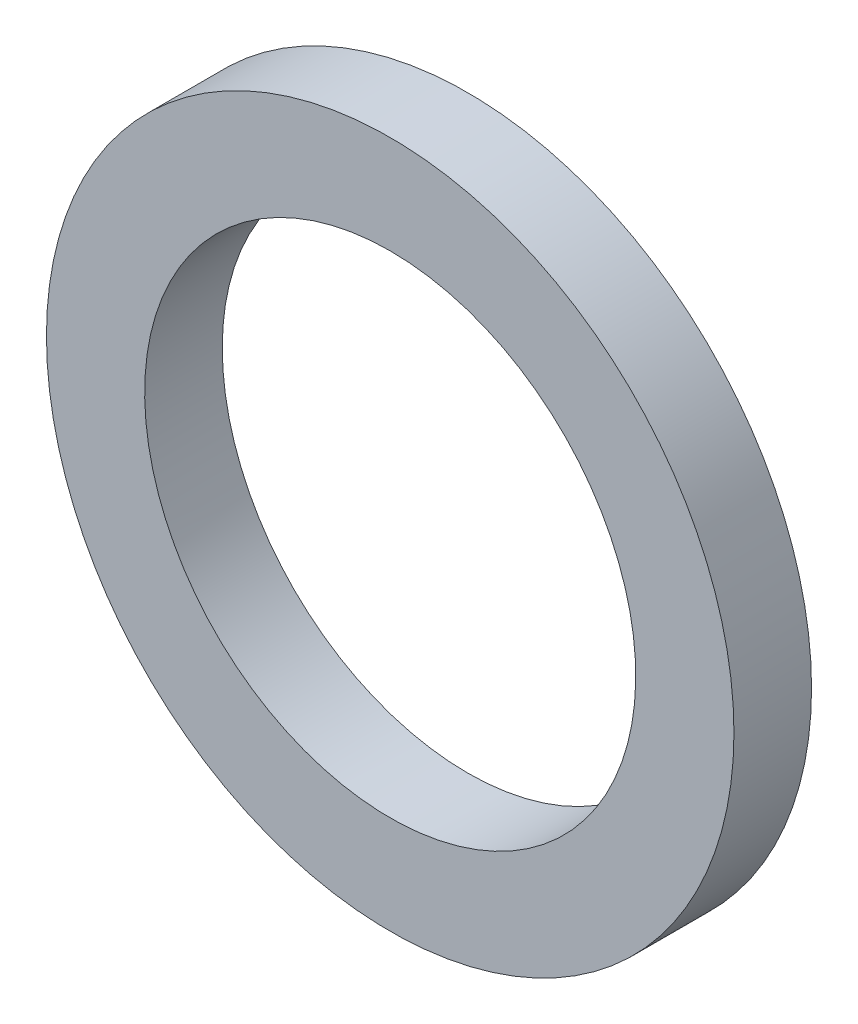
SolidWorks part; units mm, degrees
material "6061 Alloy"
ref_plane "Front Plane" through (0, 0, 0) normal (0, 0, 1) x (1, 0, 0)
ref_plane "Top Plane" through (0, 0, 0) normal (0, 1, 0) x (1, 0, 0)
ref_plane "Right Plane" through (0, 0, 0) normal (1, 0, 0) x (0, 0, -1)
sketch "Sketch1" plane through (0, 0, 0) normal (0, 0, 1) x (1, 0, 0)
  circle A0 centre (0, 0) radius 7.9375
  circle A1 centre (0, 0) radius 11.1125
  dimension "D1" = 15.875
  dimension "D2" = 22.225
extrude "Boss-Extrude1" add sketch "Sketch1" along normal up to surface (2.5081 mm away)
